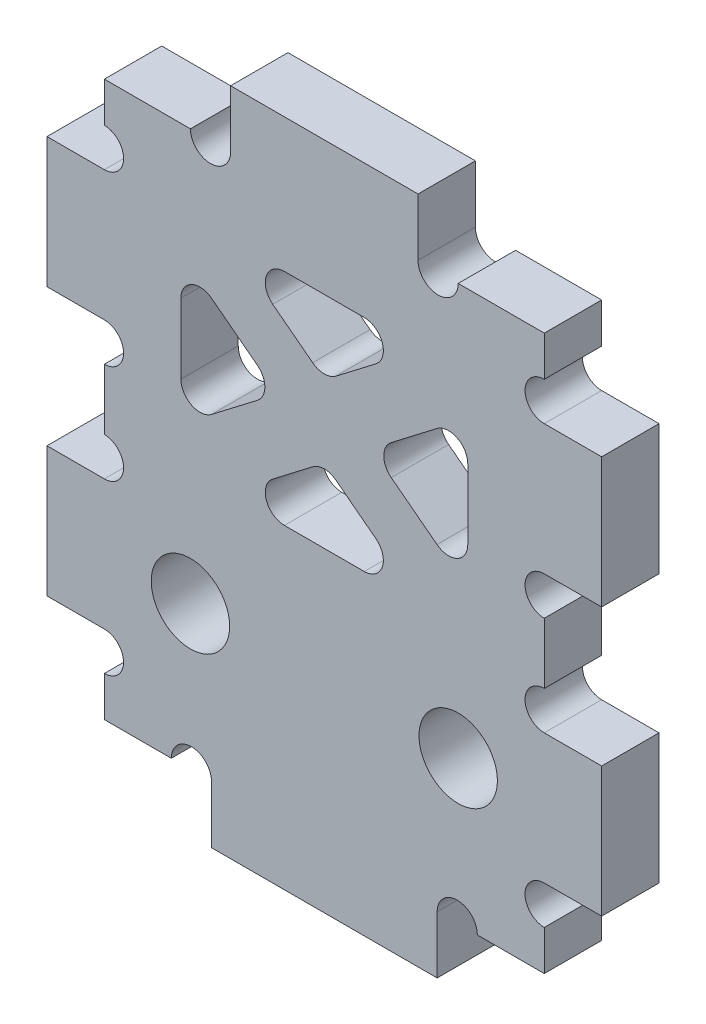
SolidWorks part; units mm, degrees
material "Thornel Mat VMA"
ref_plane "前视基准面" through (0, 0, 0) normal (0, 0, 1) x (1, 0, 0)
ref_plane "上视基准面" through (0, 0, 0) normal (0, 1, 0) x (1, 0, 0)
ref_plane "右视基准面" through (0, 0, 0) normal (1, 0, 0) x (0, 0, -1)
sketch "草图1" plane through (0, 0, 0) normal (0, 0, 1) x (1, 0, 0)
  line L0 (0, 0) -> (0, 17.5) construction
  line L1 (11.5, -14.5) -> (5.9, -14.5)
  line L2 (11.5, -14.5) -> (11.5, -10.4)
  line L3 (11.5, 14.5) -> (4.9, 14.5)
  line L4 (-11.5, -14.5) -> (-11.5, -10.4)
  line L5 (11.5, -14.5) -> (-11.5, 14.5) construction
  line L6 (11.5, 14.5) -> (-11.5, -14.5) construction
  line L7 (-4.9, 17.5) -> (4.9, 17.5)
  line L8 (4.9, 17.5) -> (4.9, 14.5)
  line L9 (-4.9, 17.5) -> (-4.9, 14.5)
  line L10 (-4.9, 14.5) -> (-11.5, 14.5)
  line L11 (0, 0) -> (13.5504, 0) construction
  line L12 (11.5, 10.4) -> (14.5, 10.4)
  line L13 (14.5, 10.4) -> (14.5, 3.6)
  line L14 (14.5, 3.6) -> (11.5, 3.6)
  line L15 (11.5, 10.4) -> (11.5, 14.5)
  line L16 (14.5, -3.6) -> (11.5, -3.6)
  line L17 (14.5, -10.4) -> (14.5, -3.6)
  line L18 (11.5, -10.4) -> (14.5, -10.4)
  line L19 (11.5, -3.6) -> (11.5, 3.6)
  line L20 (14.5, 7) -> (11.1268, 7) construction
  line L21 (14.5, -7) -> (11.1268, -7) construction
  line L22 (-5.9, -17.5) -> (5.9, -17.5)
  line L23 (-5.9, -17.5) -> (-5.9, -14.5)
  line L24 (5.9, -17.5) -> (5.9, -14.5)
  line L25 (-5.9, -14.5) -> (-11.5, -14.5)
  line L26 (-11.5, -10.4) -> (-14.5, -10.4)
  line L27 (-14.5, -10.4) -> (-14.5, -3.6)
  line L28 (-14.5, -3.6) -> (-11.5, -3.6)
  line L29 (-14.5, 3.6) -> (-11.5, 3.6)
  line L30 (-14.5, 10.4) -> (-14.5, 3.6)
  line L31 (-11.5, 10.4) -> (-14.5, 10.4)
  line L32 (-11.5, 10.4) -> (-11.5, 14.5)
  line L33 (-11.5, -3.6) -> (-11.5, 3.6)
  line L34 (7, -2) -> (20.7637, -2) construction
  line L35 (-23.92, -5) -> (24.9732, -5) construction
  line L36 (5.0346, 10.5) -> (0, 6.6401)
  line L37 (7.5, -1) -> (-7.5, -1) construction
  line L38 (7.5, -1) -> (7.5, 10.5) construction
  line L39 (7.5, 10.5) -> (-7.5, 10.5) construction
  line L40 (-7.5, -1) -> (-7.5, 10.5) construction
  line L41 (7.5, -1) -> (-7.5, 10.5) construction
  line L42 (7.5, 10.5) -> (-7.5, -1) construction
  line L43 (-5.0346, -1) -> (0, 2.8599)
  line L44 (-7.5, 8.6099) -> (-2.4654, 4.75)
  line L45 (-5.0346, 10.5) -> (0, 6.6401)
  line L46 (-7.5, 8.6099) -> (-7.5, 0.8901)
  line L47 (-5.0346, -1) -> (5.0346, -1)
  line L48 (7.5, 8.6099) -> (7.5, 0.8901)
  line L49 (-5.0346, 10.5) -> (5.0346, 10.5)
  line L50 (-2.4654, 4.75) -> (-7.5, 0.8901)
  line L51 (0, 2.8599) -> (5.0346, -1)
  line L52 (2.4654, 4.75) -> (7.5, 0.8901)
  line L53 (2.4654, 4.75) -> (7.5, 8.6099)
  circle A0 centre (5.95, 14.5) radius 1.05
  circle A1 centre (-5.95, 14.5) radius 1.05
  circle A2 centre (11.5, 11.405) radius 1.005
  circle A3 centre (11.5, 2.595) radius 1.005
  circle A4 centre (11.5, -2.595) radius 1.005
  circle A5 centre (11.5, -11.405) radius 1.005
  circle A6 centre (6.95, -14.5) radius 1.05
  circle A7 centre (-6.95, -14.5) radius 1.05
  circle A8 centre (-11.5, -11.405) radius 1.005
  circle A9 centre (-11.5, -2.595) radius 1.005
  circle A10 centre (-11.5, 2.595) radius 1.005
  circle A11 centre (-11.5, 11.405) radius 1.005
  circle A12 centre (-7, -7) radius 2.05
  circle A13 centre (7, -7) radius 2.05
  circle A14 centre (7, -7) radius 6 construction
  circle A15 centre (-7, -7) radius 6 construction
  point P0 (0, 0)
  point P70 (0, 4.75)
  dimension "D5" = 2.1
  dimension "D9" = 2.01
  dimension "D10" = 4.1
  dimension "D15" = 12
  dimension "D1" = 29
  dimension "D2" = 23
  dimension "D3" = 3
  dimension "D4" = 9.8
  dimension "D6" = 14
  dimension "D7" = 6.8
  dimension "D8" = 3
  dimension "D11" = 14
  dimension "D12" = 7
  dimension "D13" = 11.8
  dimension "D14" = 7
  dimension "D16" = 5
  dimension "D17" = 5
  dimension "D18" = 3
  dimension "D19" = 3
  dimension "D20" = 4
  dimension "D21" = 4
  dimension "D22" = 6
  dimension "D23" = 3
extrude "凸台-拉伸1" add sketch "草图1" along normal blind 3 contours L32 A11 L31 L30 L29 A10 L33 A9 L28 L27 L26 A8 L4 L25 A7 L23 L22 L24 A6 L1 L2 A5 L18 L17 L16 A4 L19 A3 L14 L13 L12 A2 L15 L3 A0 L8 L7 L9 A1 L10 A13 A12
fillet "圆角1" radius 1 12 edges at (7.5, 0.8901, 1.5) (7.5, 8.6099, 1.5) (2.4654, 4.75, 1.5) (-5.0346, -1, 1.5) (5.0346, -1, 1.5) (0, 2.8599, 1.5) (0, 6.6401, 1.5) (5.0346, 10.5, 1.5) (-5.0346, 10.5, 1.5) (-7.5, 0.8901, 1.5) (-2.4654, 4.75, 1.5) (-7.5, 8.6099, 1.5)
